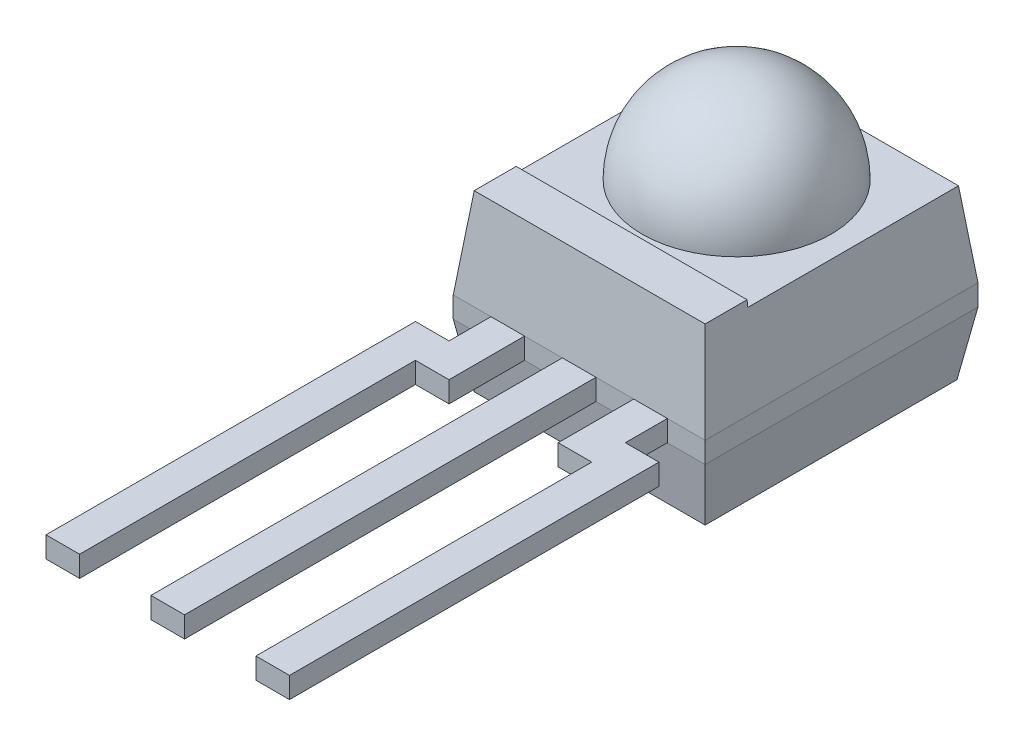
SolidWorks part; units mm, degrees
ref_plane "Front Plane" through (0, 0, 0) normal (0, 0, 1) x (1, 0, 0)
ref_plane "Top Plane" through (0, 0, 0) normal (0, 1, 0) x (1, 0, 0)
ref_plane "Right Plane" through (0, 0, 0) normal (1, 0, 0) x (0, 0, -1)
sketch "Sketch1" plane through (0, 0, 0) normal (0, 1, 0) x (1, 0, 0)
  line L1 (-3, 3.25) -> (3, 3.25)
  line L2 (-3, 3.25) -> (-3, -3.25)
  line L3 (-3, -3.25) -> (3, -3.25)
  line L4 (3, 3.25) -> (3, -3.25)
  line L5 (-3, 3.25) -> (3, -3.25) construction
  line L6 (-3, -3.25) -> (3, 3.25) construction
  point P0 (0, 0)
  dimension "D1" = 6
  dimension "D2" = 6.5
extrude "Boss-Extrude1" add sketch "Sketch1" along normal blind 4
sketch "Sketch2" plane through (0, 0, 3.25) normal (0, 0, 1) x (1, 0, 0)
  line L0 (-3, 0) -> (3, 0) construction
  line L1 (-2.1, 1.5) -> (-1.3, 1.5)
  line L2 (-2.1, 1.5) -> (-2.1, 2)
  line L3 (-2.1, 2) -> (-1.3, 2)
  line L4 (-1.3, 1.5) -> (-1.3, 2)
  line L5 (-3, 1.5) -> (-2.1, 1.5) construction
  line L6 (-0.4, 1.5) -> (0.4, 1.5)
  line L7 (-0.4, 1.5) -> (-0.4, 2)
  line L8 (-0.4, 2) -> (0.4, 2)
  line L9 (0.4, 1.5) -> (0.4, 2)
  line L10 (1.3, 1.5) -> (2.1, 1.5)
  line L11 (1.3, 1.5) -> (1.3, 2)
  line L12 (1.3, 2) -> (2.1, 2)
  line L13 (2.1, 1.5) -> (2.1, 2)
  line L14 (-3, 4) -> (-3, 0) construction
  line L15 (-1.3, 1.5) -> (-0.4, 1.5) construction
  line L16 (0.4, 1.5) -> (1.3, 1.5) construction
  line L17 (2.1, 1.5) -> (3, 1.5) construction
  line L18 (3, 4) -> (3, 0) construction
  dimension "D1" = 1.5
  dimension "D2" = 0.5
  dimension "D3" = 0.8
extrude "Boss-Extrude2" add sketch "Sketch2" along normal blind 1
sketch "Sketch3" plane through (0, 2, 0) normal (0, 1, 0) x (1, 0, 0)
  line L0 (-1.3, -4.25) -> (-1.3, -5.05)
  line L1 (-0.4, -4.25) -> (0.4, -4.25)
  line L2 (-0.4, -4.25) -> (-0.4, -13.05)
  line L3 (-0.4, -13.05) -> (0.4, -13.05)
  line L4 (0.4, -4.25) -> (0.4, -13.05)
  line L5 (-2.1, -4.25) -> (-2.9, -4.25)
  line L6 (-2.1, -5.05) -> (-2.1, -13.05)
  line L7 (-2.1, -13.05) -> (-2.9, -13.05)
  line L8 (-2.9, -4.25) -> (-2.9, -13.05)
  line L9 (-1.3, -5.05) -> (-2.1, -5.05)
  line L10 (-1.3, -4.25) -> (-2.1, -4.25)
  line L11 (1.3, -4.25) -> (2.9, -4.25)
  line L12 (2.9, -4.25) -> (2.9, -13.05)
  line L13 (2.9, -13.05) -> (2.1, -13.05)
  line L14 (2.1, -13.05) -> (2.1, -5.05)
  line L15 (2.1, -5.05) -> (1.3, -5.05)
  line L16 (1.3, -5.05) -> (1.3, -4.25)
  dimension "D1" = 8
extrude "Boss-Extrude3" add sketch "Sketch3" against normal blind 0.5
sketch "Sketch4" plane through (0, 4, 0) normal (0, 1, 0) x (1, 0, 0)
  line L0 (0, 2.75) -> (0, -1.75)
  line L1 (-3, -3.25) -> (3, -3.25) construction
  arc A0 (0, 2.75) -> (0, -1.75) centre (0, 0.5) ccw
  dimension "D1" = 1.5
  dimension "D2" = 4.5
revolve "Revolve1" add sketch "Sketch4" angle 180 about L0
sketch "Sketch5" plane through (0, 4, 0) normal (0, 1, 0) x (1, 0, 0)
  line L0 (-3, -3.25) -> (3, -3.25) construction
  line L1 (-3, -3.25) -> (3, -3.25)
  line L2 (-3, -3.25) -> (-3, -2)
  line L3 (-3, -2) -> (3, -2)
  line L4 (3, -3.25) -> (3, -2)
  line L5 (-3, 3.25) -> (-3, -3.25) construction
  line L6 (3, -3.25) -> (3, 3.25) construction
  line L7 (0, -1.75) -> (0, -2) construction
  circle A1 centre (0, 0.5) radius 2.25 construction
  dimension "D1" = 0.25
extrude "Boss-Extrude4" add sketch "Sketch5" along normal blind 0.15
sketch "Sketch6" plane through (0, 0, 3.25) normal (0, 0, 1) x (1, 0, 0)
  line L0 (-3, 2) -> (-2.75, 4.15)
  line L1 (-3, 4.15) -> (-3, 0) construction
  line L2 (-3, 4.15) -> (3, 4.15) construction
  line L3 (-2.75, 4.15) -> (-3, 4.15)
  line L4 (-3, 4.15) -> (-3, 2)
  line L5 (-2.9, 2) -> (-2.1, 2) construction
  line L6 (-3, 1.5) -> (-2.75, 0)
  line L7 (-3, 0) -> (3, 0) construction
  line L8 (-2.75, 0) -> (-3, 0)
  line L9 (-3, 0) -> (-3, 1.5)
  line L10 (-2.9, 1.5) -> (-2.1, 1.5) construction
  line L11 (0, 0) -> (0, 4.15) construction
  line L12 (3, 0) -> (3, 1.5)
  line L13 (2.75, 0) -> (3, 0)
  line L14 (3, 1.5) -> (2.75, 0)
  line L15 (3, 4.15) -> (3, 2)
  line L16 (2.75, 4.15) -> (3, 4.15)
  line L17 (3, 2) -> (2.75, 4.15)
  dimension "D1" = 0.25
extrude "Cut-Extrude1" cut sketch "Sketch6" against normal through all
sketch "Sketch7" plane through (-3, 0, 0) normal (-1, 0, 0) x (0, 0, 1)
  line L0 (3.25, 2) -> (3.25, 4.15)
  line L1 (3.25, 4.15) -> (3, 4.15)
  line L2 (2, 4.15) -> (3.25, 4.15) construction
  line L3 (3, 4.15) -> (3.25, 2)
  line L4 (3.25, 1.5) -> (3.25, 0)
  line L5 (3.25, 0) -> (3, 0)
  line L6 (-3.25, 0) -> (3.25, 0) construction
  line L7 (3, 0) -> (3.25, 1.5)
  line L8 (0, 0) -> (0, 4) construction
  line L9 (2, 4) -> (-3.25, 4) construction
  line L10 (-3, 0) -> (-3.25, 1.5)
  line L11 (-3.25, 0) -> (-3, 0)
  line L12 (-3.25, 1.5) -> (-3.25, 0)
  line L13 (-3, 4.15) -> (-3.25, 2)
  line L14 (-3.25, 4.15) -> (-3, 4.15)
  line L15 (-3.25, 2) -> (-3.25, 4.15)
  dimension "D1" = 0.25
extrude "Cut-Extrude2" cut sketch "Sketch7" against normal through all
